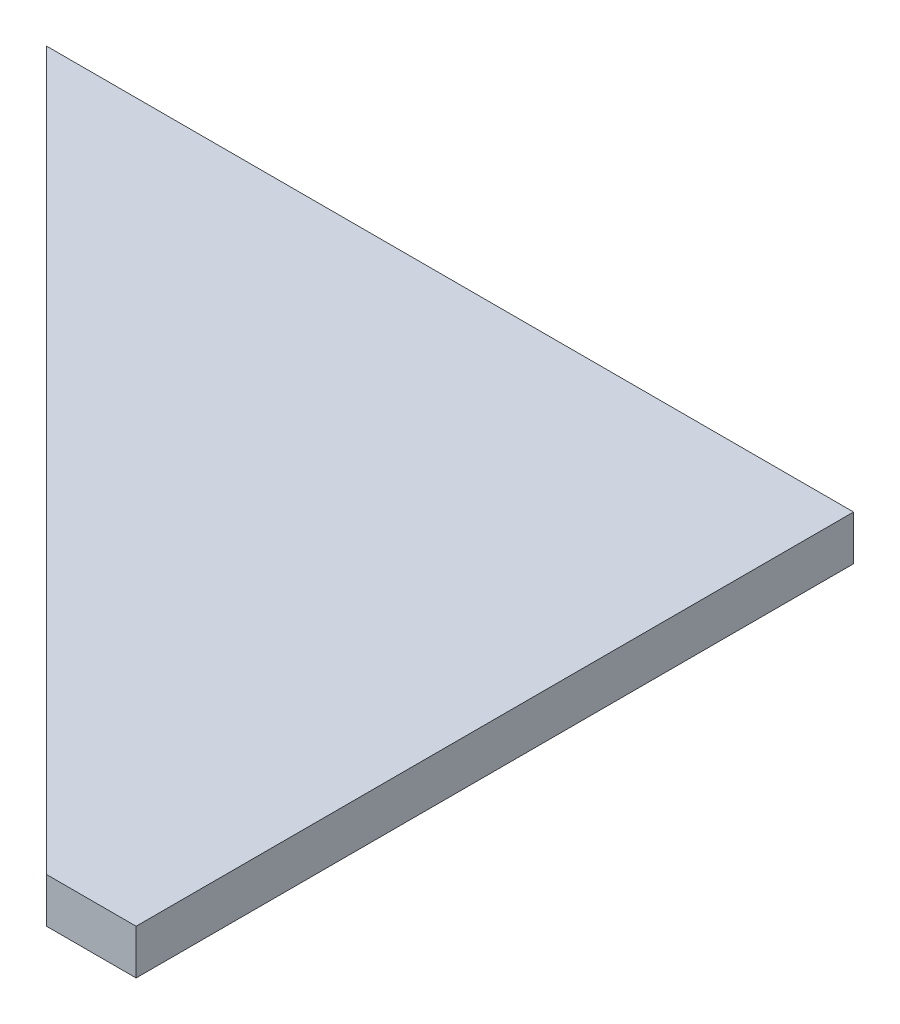
SolidWorks part; units mm, degrees
ref_plane "Front Plane" through (0, 0, 0) normal (0, 0, 1) x (1, 0, 0)
ref_plane "Top Plane" through (0, 0, 0) normal (0, 1, 0) x (1, 0, 0)
ref_plane "Right Plane" through (0, 0, 0) normal (1, 0, 0) x (0, 0, -1)
sketch "Sketch1" plane through (0, 0, 0) normal (0, 1, 0) x (1, 0, 0)
  line L0 (-6.35, -50.8) -> (-107.95, 50.8)
  line L1 (-6.35, -50.8) -> (6.35, -50.8)
  line L2 (-6.35, -50.8) -> (-6.35, 50.8)
  line L3 (-6.35, 50.8) -> (6.35, 50.8)
  line L4 (6.35, -50.8) -> (6.35, 50.8)
  line L5 (-6.35, -50.8) -> (6.35, 50.8) construction
  line L6 (-6.35, 50.8) -> (6.35, -50.8) construction
  line L7 (-107.95, 50.8) -> (-6.35, 50.8)
  point P0 (0, 0)
  dimension "D1" = 12.7
  dimension "D2" = 101.6
  dimension "D3" = 101.6
extrude "Boss-Extrude1" add sketch "Sketch1" along normal blind 6.35 contours L7 L0 L2 | L1 L4 L3 L2
